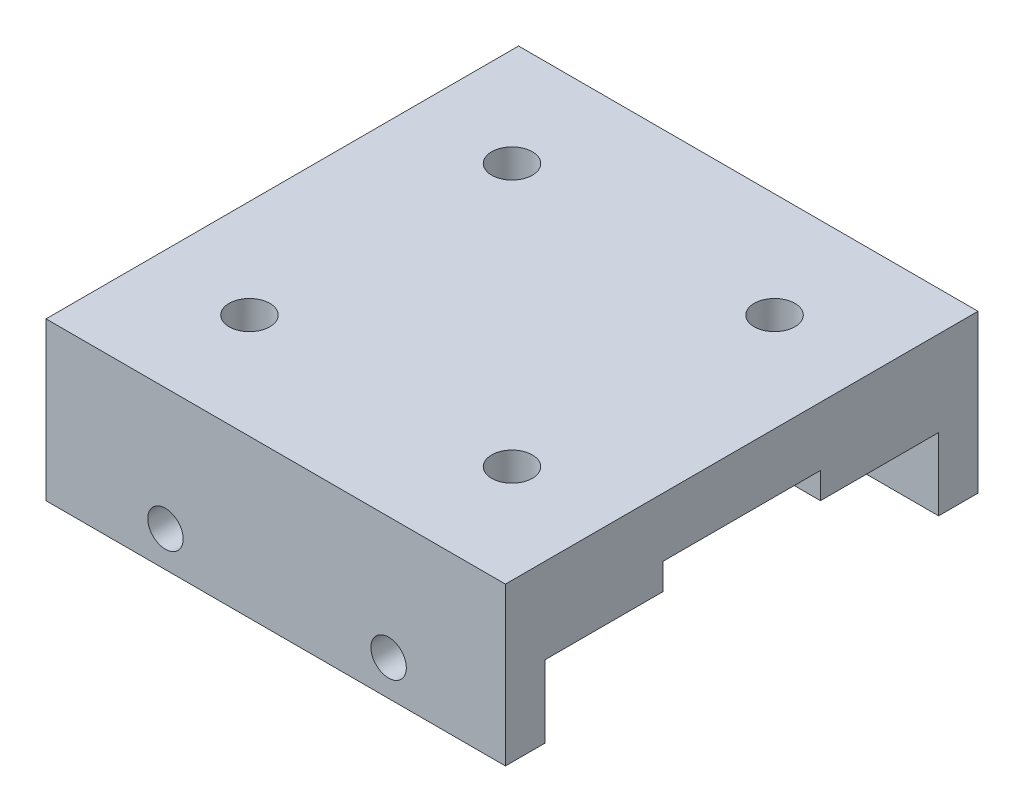
SolidWorks part; units mm, degrees
ref_plane "Front Plane" through (0, 0, 0) normal (0, 0, 1) x (1, 0, 0)
ref_plane "Top Plane" through (0, 0, 0) normal (0, 1, 0) x (1, 0, 0)
ref_plane "Right Plane" through (0, 0, 0) normal (1, 0, 0) x (0, 0, -1)
sketch "Sketch1" plane through (0, 0, 0) normal (0, 0, 1) x (1, 0, 0)
  line L8 (-9.1, 2.5) -> (25.9, 2.5) construction
  line L14 (25.9, 9.3) -> (-9.1, 9.3)
  line L15 (-9.1, 2.5) -> (-9.1, -2.7)
  line L16 (-9.1, -2.7) -> (25.9, -2.7)
  line L21 (25.9, 2.5) -> (25.9, -2.7)
  line L27 (-17, -50.9163) -> (-17, 49949.0837) construction
  line L30 (0, 0) -> (17, 0) construction
  line L32 (-9.1, 2.5) -> (-9.1, 9.3)
  line L35 (0, 0) -> (-47.3083, 0) construction
  line L36 (25.9, 9.3) -> (25.9, 2.5)
  circle A10 centre (0, 0) radius 1.35 construction
  circle A11 centre (17, 0) radius 1.35 construction
  dimension "D2" = 9.1
  dimension "D4" = 35
  dimension "D6" = 12
  dimension "D7" = 17
  dimension "D9" = 2.7
  dimension "D12" = 2.7
extrude "Boss-Extrude1" add sketch "Sketch1" along normal blind 18
sketch "Croquis2" plane through (0, 0, 18) normal (0, 0, 1) x (1, 0, 0)
  circle A0 centre (0, 0) radius 1.35
  circle A1 centre (17, 0) radius 1.35
extrude "Cortar-Extruir2" cut sketch "Croquis2" against normal blind 5
sketch "Sketch3" plane through (0, 0, 18) normal (0, 0, 1) x (1, 0, 0)
  circle A5 centre (0, 0) radius 2.25
  circle A6 centre (17, 0) radius 2.25
extrude "Cut-Extrude1" [suppressed] cut sketch "Sketch3" against normal blind 1.5
sketch "Croquis3" plane through (0, 0, 18) normal (0, 0, -1) x (-1, 0, 0)
  line L0 (-25.9, -2.7) -> (-25.9, 2.8)
  line L1 (-25.9, 2.5) -> (-25.9, -2.7) construction
  line L2 (-25.9, 2.8) -> (4.1, 2.8)
  line L4 (9.1, -2.7) -> (-25.9, -2.7)
  line L5 (9.1, -2.7) -> (-25.9, -2.7) construction
  line L7 (9.1, -2.7) -> (-25.9, -2.7) construction
  line L11 (9.1, -2.7) -> (9.1, -2.2)
  line L13 (9.1, -2.2) -> (4.1, 2.8)
  line L14 (9.1, 2.5) -> (9.1, -2.7) construction
  dimension "D2" = 45
extrude "Cortar-Extruir3" cut sketch "Croquis3" along normal blind 17 from offset 3
mirror "Mirror1" about plane through (0, 0, 0) normal (0, 0, 1) of "Boss-Extrude1", "Cortar-Extruir2", "Cortar-Extruir3"
sketch "Croquis4" plane through (0, 2.8, 0) normal (0, -1, 0) x (1, 0, 0)
  line L1 (-44.1, 6) -> (25.9, 6)
  line L2 (-44.1, 6) -> (-44.1, -6)
  line L3 (-44.1, -6) -> (25.9, -6)
  line L4 (25.9, 6) -> (25.9, -6)
  line L5 (25.9, -15) -> (25.9, 15) construction
extrude "Cortar-Extruir4" cut sketch "Croquis4" along normal through all and the other way blind 2
sketch "Croquis5" plane through (0, 2.8, 0) normal (0, -1, 0) x (1, 0, 0)
  line L0 (25.9, 0) -> (-9.1, 0) construction
  line L1 (-1.6, -10) -> (18.4, -10) construction
  line L2 (-1.6, -10) -> (-1.6, 10) construction
  line L3 (-1.6, 10) -> (18.4, 10) construction
  line L4 (18.4, -10) -> (18.4, 10) construction
  line L5 (-1.6, -10) -> (18.4, 10) construction
  line L6 (-1.6, 10) -> (18.4, -10) construction
  line L8 (-1.6, 13.1754) -> (-4.35, 11.5877)
  line L9 (-4.35, 11.5877) -> (-4.35, 8.4123)
  line L10 (-4.35, 8.4123) -> (-1.6, 6.8246)
  line L11 (-1.6, 6.8246) -> (1.15, 8.4123)
  line L12 (1.15, 8.4123) -> (1.15, 11.5877)
  line L13 (1.15, 11.5877) -> (-1.6, 13.1754)
  line L14 (18.4, 13.1754) -> (15.65, 11.5877)
  line L15 (15.65, 11.5877) -> (15.65, 8.4123)
  line L16 (15.65, 8.4123) -> (18.4, 6.8246)
  line L17 (18.4, 6.8246) -> (21.15, 8.4123)
  line L18 (21.15, 8.4123) -> (21.15, 11.5877)
  line L19 (21.15, 11.5877) -> (18.4, 13.1754)
  line L20 (-1.6, -6.8246) -> (-4.35, -8.4123)
  line L21 (-4.35, -8.4123) -> (-4.35, -11.5877)
  line L22 (-4.35, -11.5877) -> (-1.6, -13.1754)
  line L23 (-1.6, -13.1754) -> (1.15, -11.5877)
  line L24 (1.15, -11.5877) -> (1.15, -8.4123)
  line L25 (1.15, -8.4123) -> (-1.6, -6.8246)
  line L26 (18.4, -6.8246) -> (15.65, -8.4123)
  line L27 (15.65, -8.4123) -> (15.65, -11.5877)
  line L28 (15.65, -11.5877) -> (18.4, -13.1754)
  line L29 (18.4, -13.1754) -> (21.15, -11.5877)
  line L30 (21.15, -11.5877) -> (21.15, -8.4123)
  line L31 (21.15, -8.4123) -> (18.4, -6.8246)
  circle A0 centre (-1.6, 10) radius 2.75 construction
  circle A1 centre (18.4, 10) radius 2.75 construction
  circle A2 centre (-1.6, -10) radius 2.75 construction
  circle A3 centre (18.4, -10) radius 2.75 construction
  point P0 (8.4, 0)
  dimension "D3" = 5.5
  dimension "D1" = 20
  dimension "D2" = 20
extrude "Cortar-Extruir5" cut sketch "Croquis5" against normal blind 3 and the other way blind 2.5
sketch "Croquis7" plane through (0, 2.8, 0) normal (0, -1, 0) x (1, 0, 0)
  circle A0 centre (-69.5653, 7.0244) radius 0.1611
  circle A1 centre (-1.6, 10) radius 1.55
  circle A2 centre (18.4, 10) radius 1.55
  circle A3 centre (18.4, -10) radius 1.55
  circle A4 centre (-1.6, -10) radius 1.55
  dimension "D1" = 3.1
extrude "Cortar-Extruir6" cut sketch "Croquis7" against normal through all
